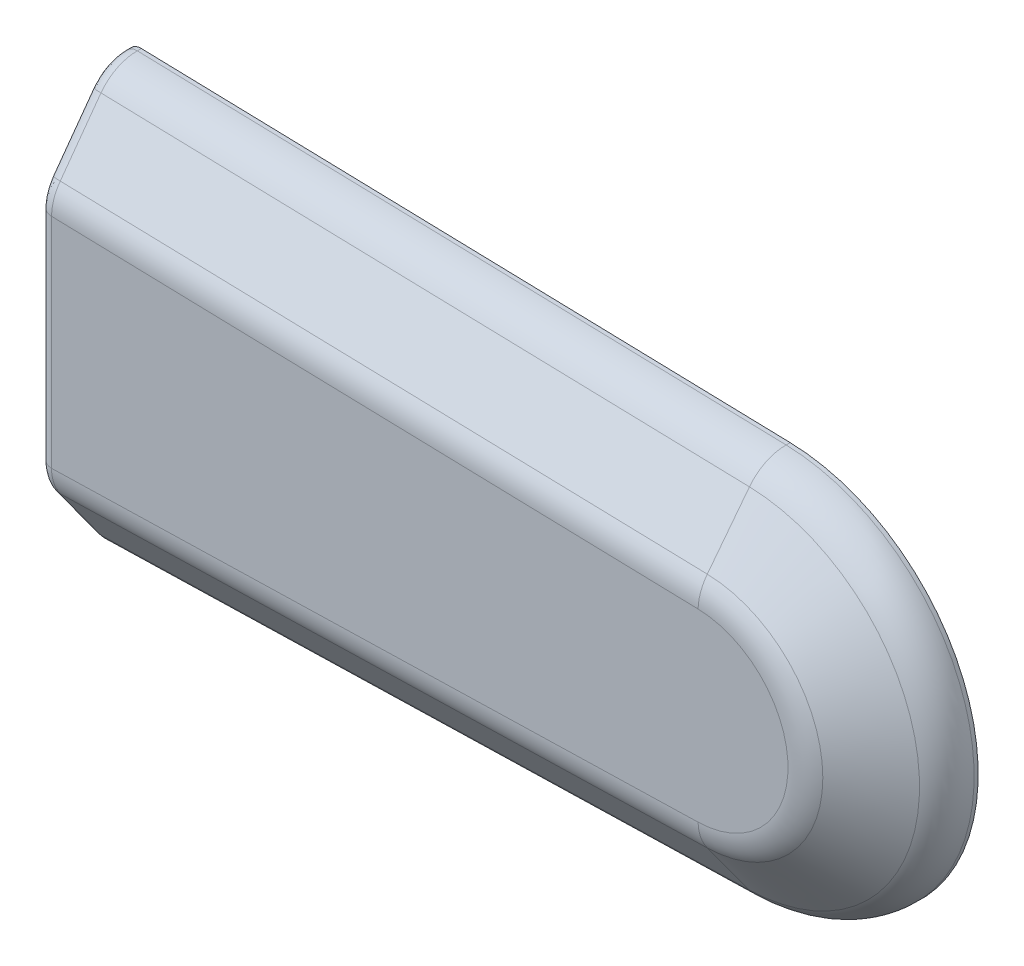
SolidWorks part; units mm, degrees
ref_plane "正面" through (0, 0, 0) normal (0, 0, 1) x (1, 0, 0)
ref_plane "平面" through (0, 0, 0) normal (0, 1, 0) x (1, 0, 0)
ref_plane "右側面" through (0, 0, 0) normal (1, 0, 0) x (0, 0, -1)
sketch "ｽｹｯﾁ1" plane through (0, 0, 0) normal (0, 0, 1) x (1, 0, 0)
  line L0 (0, 0) -> (0, 94)
  line L1 (0, 47) -> (206.2271, 47) construction
  line L2 (192, 89) -> (192, 5)
  line L3 (0, 94) -> (192, 89)
  line L4 (192, 5) -> (0, 0)
  dimension "D1" = 94
  dimension "D2" = 84
  dimension "D3" = 42
  dimension "D4" = 192
extrude "押し出し1" add sketch "ｽｹｯﾁ1" along normal blind 20
sketch "ｽｹｯﾁ2" plane through (0, 0, 20) normal (0, 0, 1) x (1, 0, 0)
  line L0 (0, 47) -> (192, 47) construction
  line L1 (0, 94) -> (0, 0) construction
  line L2 (192, 5) -> (192, 89) construction
  line L3 (147, 90.1719) -> (147, 3.8281) construction
  line L4 (192, 89) -> (0, 94) construction
  line L5 (0, 0) -> (192, 5) construction
  line L7 (147, 90.1719) -> (200.8839, 90.1719)
  line L8 (147, 90.1719) -> (147, 3.8428)
  line L9 (147, 3.8428) -> (200.8839, 3.8428)
  line L10 (200.8839, 90.1719) -> (200.8839, 3.8428)
  circle A0 centre (147, 47) radius 43.1572
  line M1 (0, 0) -> (192, 5)
  line M2 (192, 5) -> (192, 89)
  line M3 (192, 89) -> (0, 94)
  dimension "D1" = 45
extrude "ｶｯﾄ - 押し出し1" cut sketch "ｽｹｯﾁ2" against normal through all contours A0 M3 M1 M2
chamfer "面取り1" distance 14 angle 54 3 edges at (74.0618, 1.9287, 20) (190.1572, 47, 20) (74.0618, 92.0713, 20)
fillet "ﾌｨﾚｯﾄ1" radius 10 6 edges at (73.8109, 21.198, 20) (170.8879, 47, 20) (74.0618, 1.9287, 6) (190.1572, 47, 6) (73.8109, 72.802, 20) (74.0618, 92.0713, 6)
fillet "ﾌｨﾚｯﾄ2" radius 3 9 edges at (0, 0, 0.4524) (0, 1.0903, 5.4447) (0, 10.3849, 13.5425) (0, 19.435, 19.5106) (0, 47, 20) (0, 74.565, 19.5106) (0, 94, 0.4524) (0, 92.9097, 5.4447) (0, 83.6151, 13.5425)
sketch "ｽｹｯﾁ3" plane through (0, 0, 0) normal (0, 0, -1) x (-1, 0, 0)
  circle A0 centre (-147, 47) radius 2.5
  dimension "D1" = 5
extrude "ｶｯﾄ - 押し出し2" cut sketch "ｽｹｯﾁ3" against normal blind 10
